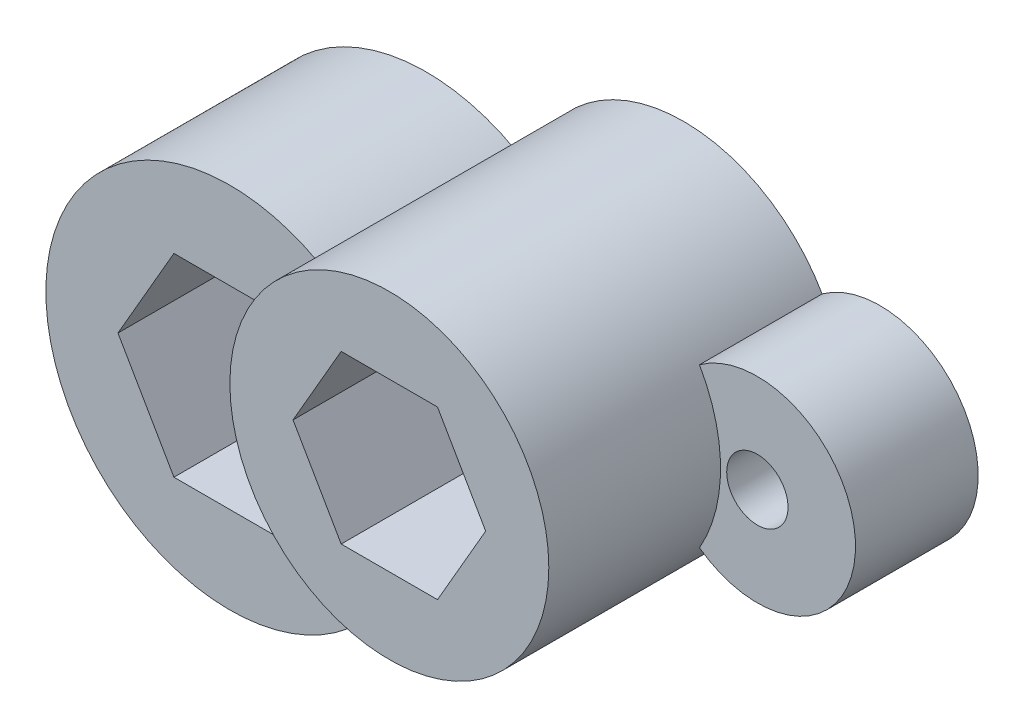
SolidWorks part; units mm, degrees
ref_plane "Front" through (0, 0, 0) normal (0, 0, 1) x (1, 0, 0)
ref_plane "Top" through (0, 0, 0) normal (0, 1, 0) x (1, 0, 0)
ref_plane "Right" through (0, 0, 0) normal (1, 0, 0) x (0, 0, -1)
sketch "Эскиз1" plane through (0, 0, 0) normal (0, 0, 1) x (1, 0, 0)
  line L1 (2.2805, -3.95) -> (4.5611, 0)
  line L2 (4.5611, 0) -> (2.2805, 3.95)
  line L3 (2.2805, 3.95) -> (-2.2805, 3.95)
  line L4 (-2.2805, 3.95) -> (-4.5611, 0)
  line L5 (-4.5611, 0) -> (-2.2805, -3.95)
  line L6 (-2.2805, -3.95) -> (2.2805, -3.95)
  circle A0 centre (0, 0) radius 7.5
  circle A1 centre (0, 0) radius 3.95 construction
  dimension "D2" = 15
  dimension "D1" = 7.9
extrude "Бобышка-Вытянуть1" add sketch "Эскиз1" along normal blind 8
sketch "Эскиз2" plane through (0, 0, 0) normal (0, 0, -1) x (-1, 0, 0)
  line L1 (-8.537, 1.1) -> (-6.574, 4.5)
  line L2 (-6.574, 4.5) -> (-8.537, 7.9)
  line L3 (-8.537, 7.9) -> (-12.463, 7.9)
  line L4 (-12.463, 7.9) -> (-14.426, 4.5)
  line L5 (-14.426, 4.5) -> (-12.463, 1.1)
  line L6 (-12.463, 1.1) -> (-8.537, 1.1)
  circle A0 centre (-10.5, 4.5) radius 3.4 construction
  circle A2 centre (-10.5, 4.5) radius 6.5
  dimension "D1" = 13
extrude "Бобышка-Вытянуть2" add sketch "Эскиз2" against normal blind 12
sketch "Эскиз3" plane through (0, 0, 0) normal (0, 0, -1) x (-1, 0, 0)
  circle A0 centre (-18.5, 4.5) radius 1.25
  circle A1 centre (-18.5, 4.5) radius 4
  dimension "D1" = 8
  dimension "D2" = 2.5
extrude "Бобышка-Вытянуть3" add sketch "Эскиз3" against normal blind 5
